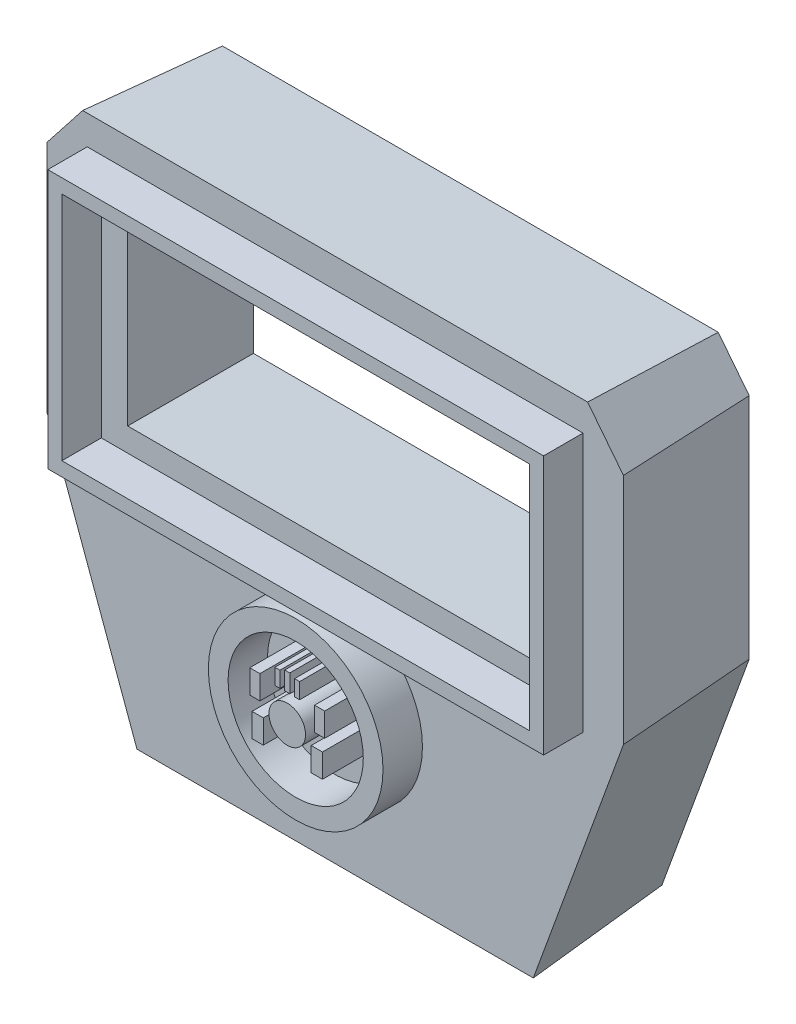
SolidWorks part; units mm, degrees
ref_plane "Front Plane" through (0, 0, 0) normal (0, 0, 1) x (1, 0, 0)
ref_plane "Top Plane" through (0, 0, 0) normal (0, 1, 0) x (1, 0, 0)
ref_plane "Right Plane" through (0, 0, 0) normal (1, 0, 0) x (0, 0, -1)
sketch "Sketch1" plane through (0, 0, 0) normal (0, 0, 1) x (1, 0, 0)
  line L0 (-88, 90) -> (88, 90)
  line L1 (88, 90) -> (99, 76)
  line L2 (99, 76) -> (99, -5)
  line L3 (99, -5) -> (68, -90)
  line L4 (68, -90) -> (-68, -90)
  line L5 (-68, -90) -> (-99, -5)
  line L6 (-99, -5) -> (-99, 76)
  line L7 (-99, 76) -> (-88, 90)
  line L9 (-77, 1) -> (77, 1)
  line L10 (-77, 1) -> (-77, 73)
  line L11 (-77, 73) -> (77, 73)
  line L12 (77, 1) -> (77, 73)
extrude "Boss-Extrude1" add sketch "Sketch1" along normal blind 48 draft 4 draft outward yes
sketch "Sketch2" plane through (0, 0, 0) normal (0, 0, 1) x (1, 0, 0)
  line L1 (-88, -9) -> (88, -9)
  line L2 (-88, -9) -> (-88, 83)
  line L3 (-88, 83) -> (88, 83)
  line L4 (88, -9) -> (88, 83)
  line L6 (-83, -4) -> (83, -4)
  line L7 (-83, -4) -> (-83, 78)
  line L8 (-83, 78) -> (83, 78)
  line L9 (83, -4) -> (83, 78)
  circle A0 centre (0, -42) radius 31
  circle A1 centre (0, -42) radius 24
extrude "Boss-Extrude2" add sketch "Sketch2" along normal blind 62
sketch "Sketch3" plane through (0, 0, 0) normal (0, 0, 1) x (1, 0, 0)
  line L1 (-4.4, -32.3) -> (-2.6, -32.3)
  line L2 (-4.4, -32.3) -> (-4.4, -26.7)
  line L3 (-4.4, -26.7) -> (-2.6, -26.7)
  line L4 (-2.6, -32.3) -> (-2.6, -26.7)
  line L6 (-0.9, -32.2) -> (0.9, -32.2)
  line L7 (-0.9, -32.2) -> (-0.9, -25.8)
  line L8 (-0.9, -25.8) -> (0.9, -25.8)
  line L9 (0.9, -32.2) -> (0.9, -25.8)
  line L11 (2.6, -32.3) -> (4.4, -32.3)
  line L12 (2.6, -32.3) -> (2.6, -26.7)
  line L13 (2.6, -26.7) -> (4.4, -26.7)
  line L14 (4.4, -32.3) -> (4.4, -26.7)
  line L16 (-13.3, -39.7) -> (-9.7, -39.7)
  line L17 (-13.3, -39.7) -> (-13.3, -31.3)
  line L18 (-13.3, -31.3) -> (-9.7, -31.3)
  line L19 (-9.7, -39.7) -> (-9.7, -31.3)
  line L21 (9.7, -39.7) -> (13.3, -39.7)
  line L22 (9.7, -39.7) -> (9.7, -31.3)
  line L23 (9.7, -31.3) -> (13.3, -31.3)
  line L24 (13.3, -39.7) -> (13.3, -31.3)
  line L26 (-12.5, -52.7) -> (-8.5, -52.7)
  line L27 (-12.5, -52.7) -> (-12.5, -44.3)
  line L28 (-12.5, -44.3) -> (-8.5, -44.3)
  line L29 (-8.5, -52.7) -> (-8.5, -44.3)
  line L31 (8.5, -52.7) -> (12.5, -52.7)
  line L32 (8.5, -52.7) -> (8.5, -44.3)
  line L33 (8.5, -44.3) -> (12.5, -44.3)
  line L34 (12.5, -52.7) -> (12.5, -44.3)
  circle A0 centre (0, -42) radius 6.5
extrude "Boss-Extrude3" add sketch "Sketch3" along normal blind 65
